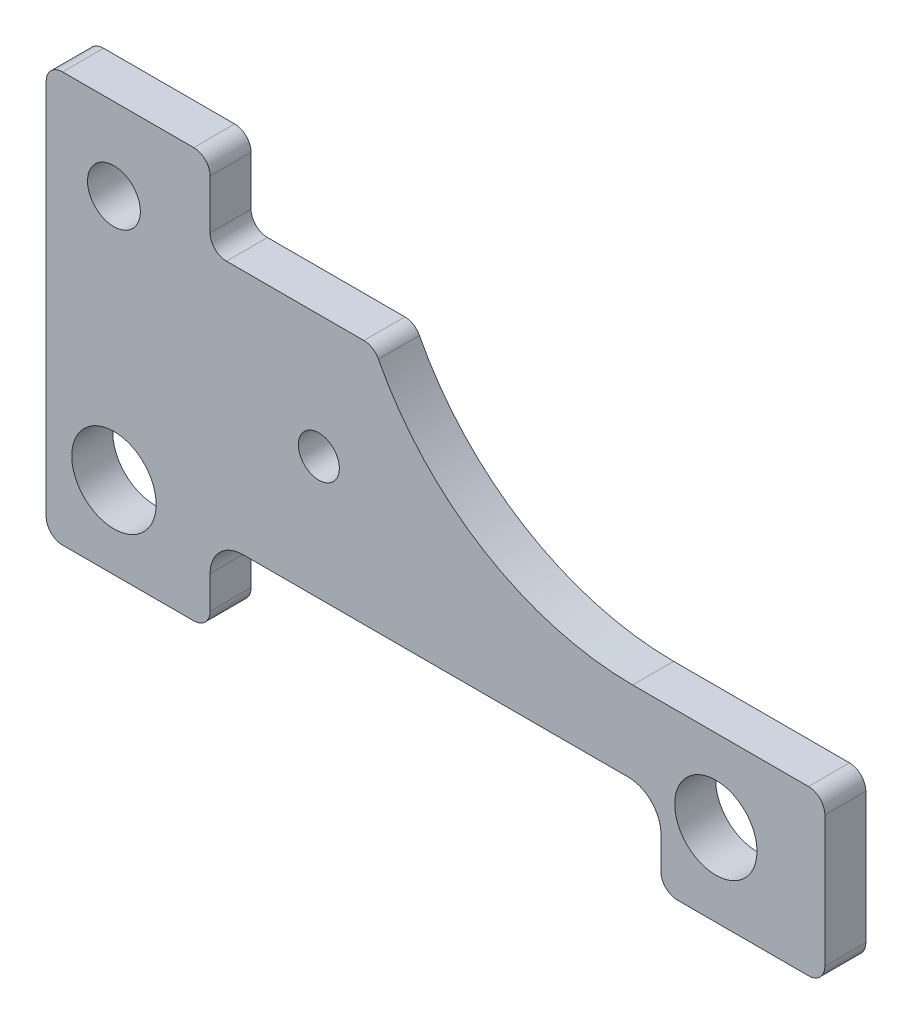
SolidWorks part; units mm, degrees
ref_plane "Front Plane" through (0, 0, 0) normal (0, 0, 1) x (1, 0, 0)
ref_plane "Top Plane" through (0, 0, 0) normal (0, 1, 0) x (1, 0, 0)
ref_plane "Right Plane" through (0, 0, 0) normal (1, 0, 0) x (0, 0, -1)
sketch "Sketch1" plane through (0, 0, 0) normal (0, 0, 1) x (1, 0, 0)
  line L0 (-63.4343, 0) -> (134.0395, 0) construction
  line L1 (4.2424, -15) -> (35.2424, -15)
  line L2 (-33.7576, 25) -> (-17.7576, 25)
  line L3 (-35.7576, 23) -> (-35.7576, -23)
  line L4 (-33.7576, -25) -> (-17.7576, -25)
  line L5 (-15.7576, 23) -> (-15.7576, 17)
  line L6 (-13.7576, 15) -> (3.0018, 15)
  line L8 (-11.7576, -15) -> (4.2424, -15)
  line L10 (39.2424, -19) -> (39.2424, -23)
  line L11 (41.2424, -25) -> (57.2424, -25)
  line L12 (59.2424, -23) -> (59.2424, -7)
  line L13 (57.2424, -5) -> (35.7927, -5)
  line L14 (-15.7576, -19) -> (-15.7576, -23)
  circle A0 centre (45.9441, -15) radius 5.0181
  circle A1 centre (-27.4903, -15) radius 5.15
  circle A2 centre (-27.4903, 15) radius 3.225
  arc A3 (4.7782, 13.9189) -> (35.7927, -5) centre (35.8652, 29.9999) ccw
  arc A4 (4.7782, 13.9189) -> (3.0018, 15) centre (3.0018, 13) ccw
  arc A5 (-17.7576, 25) -> (-15.7576, 23) centre (-17.7576, 23) cw
  arc A6 (-35.7576, 23) -> (-33.7576, 25) centre (-33.7576, 23) cw
  arc A7 (-33.7576, -25) -> (-35.7576, -23) centre (-33.7576, -23) cw
  arc A8 (-17.7576, -25) -> (-15.7576, -23) centre (-17.7576, -23) ccw
  arc A9 (-15.7576, -19) -> (-11.7576, -15) centre (-11.7576, -19) cw
  arc A10 (35.2424, -15) -> (39.2424, -19) centre (35.2424, -19) cw
  arc A11 (57.2424, -5) -> (59.2424, -7) centre (57.2424, -7) cw
  arc A12 (57.2424, -25) -> (59.2424, -23) centre (57.2424, -23) ccw
  arc A13 (41.2424, -25) -> (39.2424, -23) centre (41.2424, -23) cw
  arc A14 (-15.7576, 17) -> (-13.7576, 15) centre (-13.7576, 17) ccw
  circle A15 centre (-2.4903, 0) radius 2.5
  point P27 (-15.7576, 25)
  point P30 (-35.7576, 25)
  point P33 (-35.7576, -25)
  point P36 (-15.7576, -25)
  point P43 (59.2424, -5)
  point P46 (59.2424, -25)
  point P49 (39.2424, -25)
  point P52 (-15.7576, 15)
  dimension "D7" = 20
  dimension "D9" = 10.3
  dimension "D10" = 6.45
  dimension "D12" = 35
  dimension "D11" = 2
  dimension "D13" = 2
  dimension "D14" = 2
  dimension "D15" = 2
  dimension "D16" = 2
  dimension "D17" = 4
  dimension "D18" = 4
  dimension "D19" = 2
  dimension "D20" = 2
  dimension "D21" = 5
  dimension "D1" = 20
  dimension "D2" = 50
  dimension "D3" = 30
  dimension "D4" = 10
  dimension "D5" = 10
  dimension "D6" = 55
  dimension "D8" = 20
  dimension "D22" = 25
extrude "Boss-Extrude1" add sketch "Sketch1" along normal blind 5
